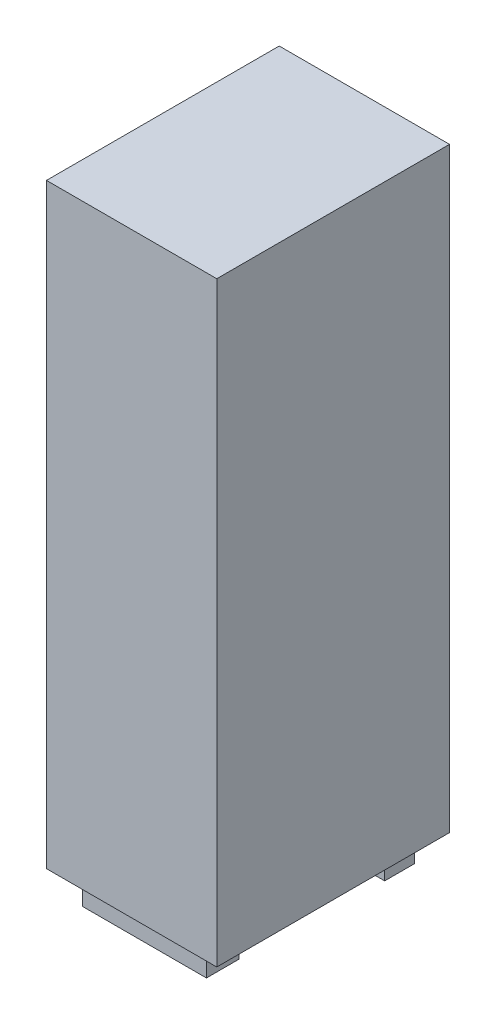
SolidWorks part; units mm, degrees
ref_plane "前视基准面" through (0, 0, 0) normal (0, 0, 1) x (1, 0, 0)
ref_plane "上视基准面" through (0, 0, 0) normal (0, 1, 0) x (1, 0, 0)
ref_plane "右视基准面" through (0, 0, 0) normal (1, 0, 0) x (0, 0, -1)
sketch "Sketch1" plane through (0, 0, 0) normal (0, 1, 0) x (1, 0, 0)
  line L1 (-15, 20.5) -> (15, 20.5)
  line L2 (-15, 20.5) -> (-15, -20.5)
  line L3 (-15, -20.5) -> (15, -20.5)
  line L4 (15, 20.5) -> (15, -20.5)
  line L5 (-15, 20.5) -> (15, -20.5) construction
  line L6 (-15, -20.5) -> (15, 20.5) construction
  point P0 (0, 0)
  dimension "D1" = 41
  dimension "D2" = 30
extrude "Boss-Extrude1" add sketch "Sketch1" along normal blind 105
sketch "Sketch2" plane through (0, 0, 0) normal (0, -1, 0) x (1, 0, 0)
  line L1 (-11.0358, 18.0849) -> (10.7662, 18.0849)
  line L2 (-11.0358, 18.0849) -> (-11.0358, 12.384)
  line L3 (-11.0358, 12.384) -> (10.7662, 12.384)
  line L4 (10.7662, 18.0849) -> (10.7662, 12.384)
  line L5 (-10.7277, -12.4225) -> (11.6521, -12.4225)
  line L6 (-10.7277, -12.4225) -> (-10.7277, -17.6997)
  line L7 (-10.7277, -17.6997) -> (11.6521, -17.6997)
  line L8 (11.6521, -12.4225) -> (11.6521, -17.6997)
extrude "Boss-Extrude2" add sketch "Sketch2" along normal blind 5
